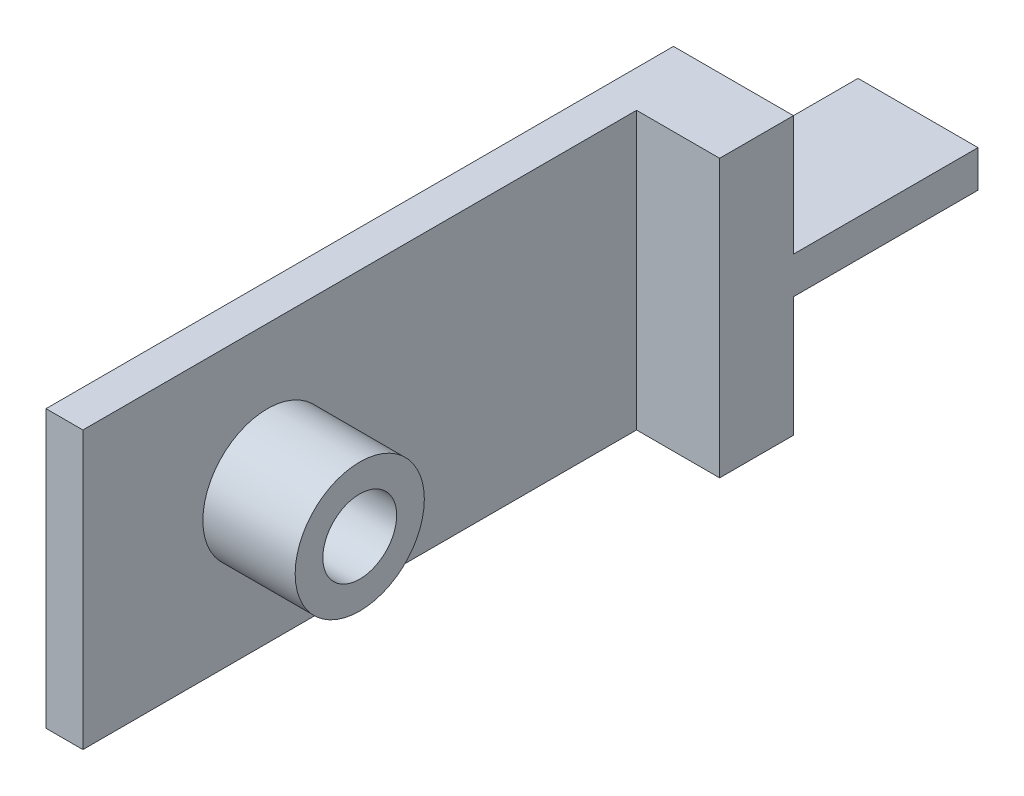
SolidWorks part; units mm, degrees
ref_plane "Front Plane" through (0, 0, 0) normal (0, 0, 1) x (1, 0, 0)
ref_plane "Top Plane" through (0, 0, 0) normal (0, 1, 0) x (1, 0, 0)
ref_plane "Right Plane" through (0, 0, 0) normal (1, 0, 0) x (0, 0, -1)
sketch "Sketch1" plane through (0, 0, 0) normal (1, 0, 0) x (0, 0, -1)
  line L1 (0, 0) -> (30, 0)
  line L2 (0, 0) -> (0, 15)
  line L3 (0, 15) -> (30, 15)
  line L4 (30, 0) -> (30, 15)
  dimension "D1" = 15
  dimension "D2" = 30
extrude "Boss-Extrude1" add sketch "Sketch1" along normal blind 2
sketch "Sketch2" plane through (0, 0, -30) normal (0, 0, -1) x (-1, 0, 0)
  line L1 (0, 15) -> (-6.5, 15)
  line L2 (0, 15) -> (0, 0)
  line L3 (0, 0) -> (-6.5, 0)
  line L4 (-6.5, 15) -> (-6.5, 0)
  dimension "D1" = 6.5
extrude "Boss-Extrude2" add sketch "Sketch2" along normal blind 4
sketch "Sketch3" plane through (0, 0, -34) normal (0, 0, -1) x (-1, 0, 0)
  line L0 (-6.5, 15) -> (-6.5, 0) construction
  line L1 (-6.5, 8.5) -> (0, 8.5)
  line L2 (-6.5, 8.5) -> (-6.5, 6.5)
  line L3 (-6.5, 6.5) -> (0, 6.5)
  line L4 (0, 8.5) -> (0, 6.5)
  line L5 (0, 0) -> (0, 15) construction
  point P8 (-6.5, 7.5)
  dimension "D1" = 2
  dimension "D2" = 7.5
extrude "Boss-Extrude3" add sketch "Sketch3" along normal blind 10
sketch "Sketch4" plane through (2, 0, 0) normal (1, 0, 0) x (0, 0, -1)
  circle A0 centre (10, 7.5) radius 2
  dimension "D2" = 4
  dimension "D1" = 20
extrude "Cut-Extrude2" cut sketch "Sketch4" against normal blind 5 contours A0
sketch "Sketch5" plane through (2, 0, 0) normal (1, 0, 0) x (0, 0, -1)
  circle A0 centre (10, 7.5) radius 2
  circle A1 centre (10, 7.5) radius 3.5
  circle A2 centre (10, 7.5) radius 2
  circle M1 centre (10, 7.5) radius 2
  dimension "D1" = 7
extrude "Boss-Extrude4" add sketch "Sketch5" along normal blind 5 contours A1 M1
